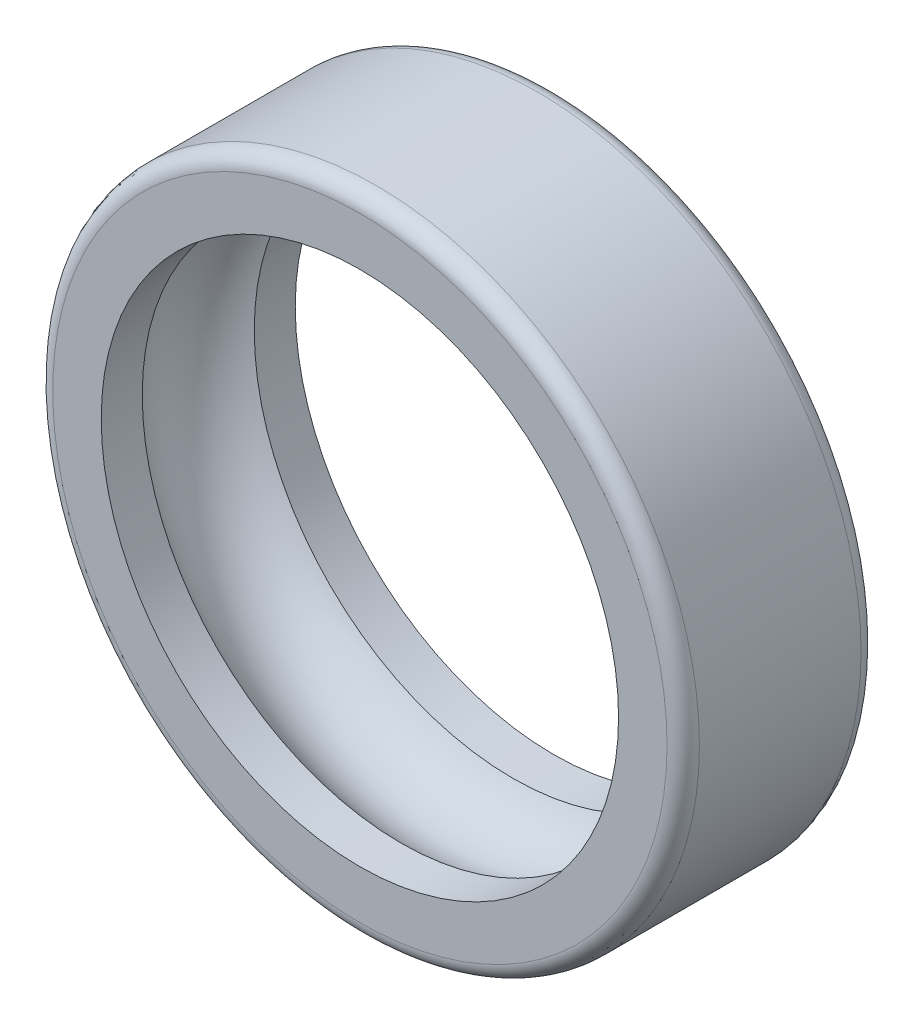
SolidWorks part; units mm, degrees
ref_plane "Front Plane" through (0, 0, 0) normal (0, 0, 1) x (1, 0, 0)
ref_plane "Top Plane" through (0, 0, 0) normal (0, 1, 0) x (1, 0, 0)
ref_plane "Right Plane" through (0, 0, 0) normal (1, 0, 0) x (0, 0, -1)
sketch "Sketch1" plane through (0, 0, 0) normal (0, 0, 1) x (1, 0, 0)
  circle A0 centre (0, 0) radius 10
  circle A1 centre (0, 0) radius 8
  dimension "D1" = 20
  dimension "D2" = 16
extrude "Boss-Extrude1" add sketch "Sketch1" along normal mid plane 6
sketch "Sketch2" plane through (0, 0, 0) normal (0, 1, 0) x (1, 0, 0)
  line L0 (-3.5218, 0) -> (3.8897, 0) construction
  line L1 (0, 1.8003) -> (0, -1.6952) construction
  circle A0 centre (-7, 0) radius 2
  dimension "D1" = 4
  dimension "D2" = 7
revolve "Cut-Revolve1" cut sketch "Sketch2" angle 360 about L1
fillet "Fillet1" radius 0.5 2 edges at (10, 0, -3) (10, 0, 3)
